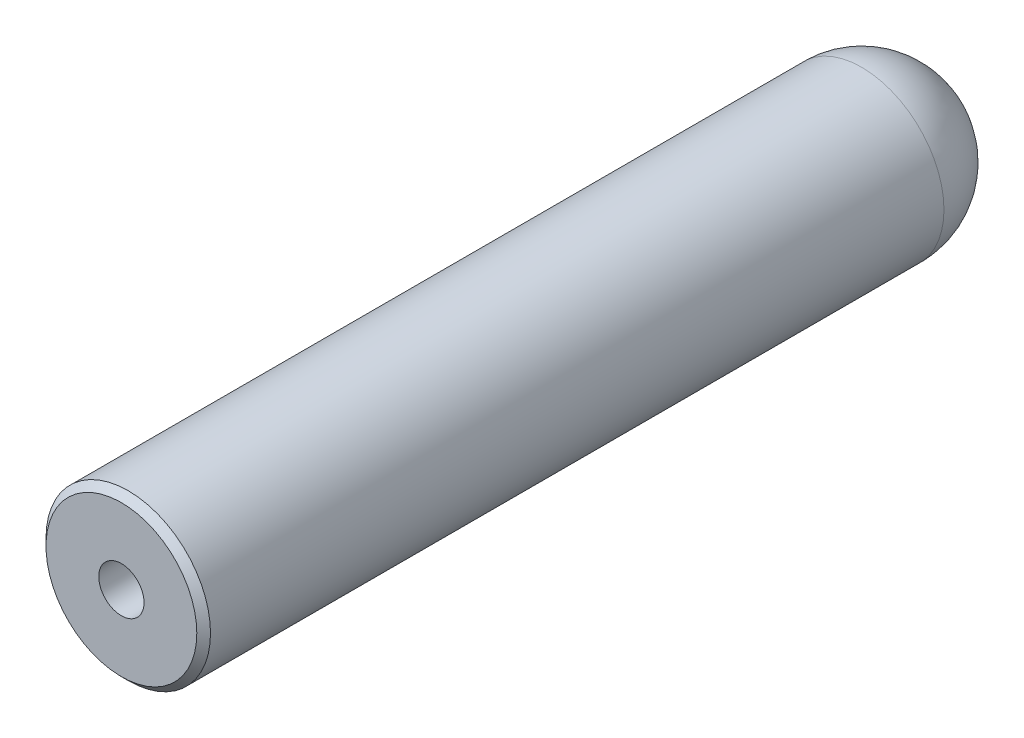
SolidWorks part; units mm, degrees
other "细节项目6"
ref_plane "前基準面" through (0, 0, 0) normal (0, 0, 1) x (1, 0, 0)
ref_plane "上基準面" through (0, 0, 0) normal (0, 1, 0) x (1, 0, 0)
ref_plane "右基準面" through (0, 0, 0) normal (1, 0, 0) x (0, 0, -1)
sketch "草圖1" plane through (0, 0, 0) normal (0, 0, 1) x (1, 0, 0)
  circle A0 centre (0, 0) radius 6
  dimension "D1" = 12
extrude "伸長1" add sketch "草圖1" along normal blind 60
fillet "圓角1" radius 6 1 edges at (6, 0, 0)
chamfer "導角1" distance 0.5 angle 45 1 edges at (6, 0, 60)
hole_wizard "M4 螺紋孔1" positions "3D草圖1" profile "草圖2" tap size "M4" standard "ISO"
sketch3d "3D草圖1"
  circle A0 centre (0, 0, 59.5) radius 6 construction
  circle A1 centre (0, 0, 6) radius 6 construction
  point P0 (0, 0, 60)
  point P5 (0, 0, 53.5)
  point P8 (0, 0, 12)
sketch "草圖2" plane through (0, 0, 60) normal (1, 0, 0) x (0, -1, 0)
  line L0 (0, 0) -> (0, 12.4914)
  line L1 (0, 12.4914) -> (1.65, 11.5)
  line L2 (1.65, 11.5) -> (1.65, 0)
  line L5 (1.65, 0) -> (0, 0)
  line L10 (0, 12.4914) -> (-1.65, 11.5) construction
  line L11 (0, -6.35) -> (0, 107.95) construction
  dimension "螺孔鑽直徑" = 3.3
  dimension "螺孔鑽深度" = 11.5
  dimension "導頭角度" = 118
cosmetic thread "鑽孔螺紋1"
